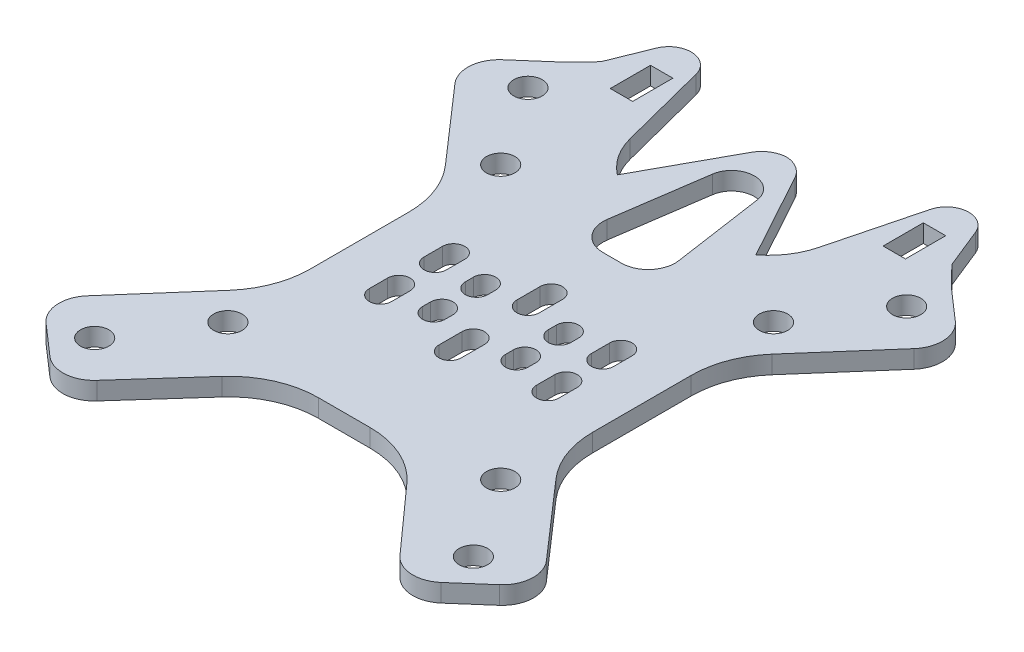
SolidWorks part; units mm, degrees
ref_plane "Alzado" through (0, 0, 0) normal (0, 0, 1) x (1, 0, 0)
ref_plane "Planta" through (0, 0, 0) normal (0, 1, 0) x (1, 0, 0)
ref_plane "Vista lateral" through (0, 0, 0) normal (1, 0, 0) x (0, 0, -1)
sketch "Croquis2" plane through (0, 0, 0) normal (0, 1, 0) x (1, 0, 0)
  line L0 (0, 0) -> (0, 10.4123) construction
  line L5 (0, 0) -> (-13.8586, 0) construction
  line L7 (-18.2653, -12.0856) -> (-25.6658, -20.5534)
  line L14 (-15.7949, 5.505) -> (-15.7949, -5.505)
  line L16 (15.7949, 5.505) -> (15.7949, -5.505)
  line L17 (-15.9969, 16.6536) -> (15.9969, -16.6536) construction
  line L18 (-14.5936, -16.6982) -> (14.5936, 16.6982) construction
  line L20 (-25.3337, -25.492) -> (-21.87, -28.5191)
  line L21 (18.2653, -12.0856) -> (25.6658, -20.5534)
  line L23 (25.3337, -25.492) -> (21.87, -28.5191)
  line L24 (25.3337, 25.492) -> (21.87, 28.5191)
  line L25 (15.4321, 26.7753) -> (15.4536, 26.7998)
  line L26 (18.2653, 12.0856) -> (25.6658, 20.5534)
  line L27 (-25.3337, 25.492) -> (-21.87, 28.5191)
  line L29 (-9.3499, 4.0906) -> (-9.3499, 2.0372) construction
  line L30 (-18.2653, 12.0856) -> (-25.6658, 20.5534)
  line L31 (-21.1669, 24.2194) -> (-23.6019, 27.0055)
  line L36 (-16.5, 33.2505) -> (-14, 33.2505)
  line L37 (-16.5, 33.2505) -> (-16.5, 28.7505)
  line L38 (-16.5, 28.7505) -> (-14, 28.7505)
  line L39 (-14, 33.2505) -> (-14, 28.7505)
  line L45 (-4.6372, 2.84) -> (-4.6372, 1.9423) construction
  line L50 (-8.0999, 4.0906) -> (-8.0999, 2.0372)
  line L51 (-10.5999, 4.0906) -> (-10.5999, 2.0372)
  line L52 (-3.3872, 2.84) -> (-3.3872, 1.9423)
  line L53 (-9.3499, -4.0906) -> (-9.3499, -2.0372) construction
  line L54 (-8.0999, -4.0906) -> (-8.0999, -2.0372)
  line L55 (-10.5999, -4.0906) -> (-10.5999, -2.0372)
  line L56 (-5.8872, 2.84) -> (-5.8872, 1.9423)
  line L57 (-10.5379, 25.0163) -> (-13.0924, 34.9381)
  line L58 (-4.6372, -2.84) -> (-4.6372, -1.9423) construction
  line L59 (-3.3872, -2.84) -> (-3.3872, -1.9423)
  line L60 (-5.8872, -2.84) -> (-5.8872, -1.9423)
  line L61 (9.3499, 4.0906) -> (9.3499, 2.0372) construction
  line L62 (8.0999, 4.0906) -> (8.0999, 2.0372)
  line L63 (10.5999, 4.0906) -> (10.5999, 2.0372)
  line L64 (4.6372, 2.84) -> (4.6372, 1.9423) construction
  line L65 (3.3872, 2.84) -> (3.3872, 1.9423)
  line L66 (5.8872, 2.84) -> (5.8872, 1.9423)
  line L67 (9.3499, -4.0906) -> (9.3499, -2.0372) construction
  line L68 (8.0999, -4.0906) -> (8.0999, -2.0372)
  line L69 (10.5999, -4.0906) -> (10.5999, -2.0372)
  line L70 (4.6372, -2.84) -> (4.6372, -1.9423) construction
  line L71 (3.3872, -2.84) -> (3.3872, -1.9423)
  line L72 (5.8872, -2.84) -> (5.8872, -1.9423)
  line L74 (0, 87.5) -> (0, -87.5) construction
  line L77 (-17.8315, 35.2509) -> (-19.6241, 30.812)
  line L78 (16.5, 28.7505) -> (14, 28.7505)
  line L79 (16.5, 33.2505) -> (16.5, 28.7505)
  line L80 (14, 33.2505) -> (14, 28.7505)
  line L81 (-54.7575, 71.0121) -> (-10.9896, 20.9323) construction
  line L82 (-23.4827, 26.1265) -> (-13.501, 38.2475) construction
  line L83 (25.3337, 25.492) -> (21.87, 28.5191)
  line L84 (-19.6241, 30.812) -> (-21.87, 28.5191)
  line L85 (16.5, 33.2505) -> (14, 33.2505)
  line L87 (19.6241, 30.812) -> (21.87, 28.5191)
  line L88 (17.8315, 35.2509) -> (19.6241, 30.812)
  line L89 (10.7473, 25.8297) -> (13.0924, 34.9381)
  line L90 (-1.0018, 28.1672) -> (1.0018, 28.1672) construction
  line L91 (-16.9315, -28.1869) -> (-10.3397, -20.824)
  line L92 (-2.8893, -17.4942) -> (2.8893, -17.4942)
  line L93 (10.3397, -20.824) -> (16.9315, -28.1869)
  line L94 (0, -5.6537) -> (0, -3.0639) construction
  line L95 (-1.25, -5.6537) -> (-1.25, -3.0639)
  line L96 (1.25, -5.6537) -> (1.25, -3.0639)
  line L97 (0, 5.6537) -> (0, 3.0639) construction
  line L98 (-1.25, 5.6537) -> (-1.25, 3.0639)
  line L99 (1.25, 5.6537) -> (1.25, 3.0639)
  line L100 (-7.7425, 20.7891) -> (-2.4628, 30.4274)
  line L101 (0.1683, 31.9861) -> (1.6089, 31.9861)
  line L102 (1.6089, 31.9861) -> (-1.6089, 31.9861) construction
  line L103 (1.0311, 12.4669) -> (-1.0311, 12.4669)
  line L104 (-3.9997, 15.8997) -> (-2.5002, 26.1856)
  line L105 (3.9997, 15.8997) -> (2.5002, 26.1856)
  line L106 (10.5379, 25.0163) -> (13.0924, 34.9381)
  line L107 (7.7425, 20.7891) -> (2.4628, 30.4274)
  circle A13 centre (-15.25, 15.25) radius 1.59
  circle A14 centre (15.25, 15.25) radius 1.59
  circle A15 centre (15.25, -15.25) radius 1.59
  circle A16 centre (-15.25, -15.25) radius 1.59
  arc A19 (-16.9315, -28.1869) -> (-21.87, -28.5191) centre (-19.5668, -25.8837) cw
  arc A20 (-25.3337, -25.492) -> (-25.6658, -20.5534) centre (-23.0305, -22.8566) cw
  arc A21 (25.3337, -25.492) -> (25.6658, -20.5534) centre (23.0305, -22.8566) ccw
  arc A22 (16.9315, -28.1869) -> (21.87, -28.5191) centre (19.5668, -25.8837) ccw
  arc A24 (25.3337, 25.492) -> (25.6658, 20.5534) centre (23.0305, 22.8566) cw
  arc A25 (-25.3337, 25.492) -> (-25.6658, 20.5534) centre (-23.0305, 22.8566) ccw
  circle A27 centre (-21.1669, 24.2194) radius 1.5875
  circle A28 centre (21.1669, 24.2194) radius 1.5875
  circle A29 centre (21.1669, -24.2194) radius 1.5875
  circle A30 centre (-21.1669, -24.2194) radius 1.5875
  circle A33 centre (21.1669, -24.2194) radius 1.5875
  arc A41 (-8.0999, 4.0906) -> (-10.5999, 4.0906) centre (-9.3499, 4.0906) ccw
  arc A42 (-10.5999, 2.0372) -> (-8.0999, 2.0372) centre (-9.3499, 2.0372) ccw
  arc A43 (-8.0999, -4.0906) -> (-10.5999, -4.0906) centre (-9.3499, -4.0906) cw
  arc A44 (-10.5999, -2.0372) -> (-8.0999, -2.0372) centre (-9.3499, -2.0372) cw
  arc A45 (-3.3872, 2.84) -> (-5.8872, 2.84) centre (-4.6372, 2.84) ccw
  arc A46 (-5.8872, 1.9423) -> (-3.3872, 1.9423) centre (-4.6372, 1.9423) ccw
  arc A47 (-3.3872, -2.84) -> (-5.8872, -2.84) centre (-4.6372, -2.84) cw
  arc A48 (-5.8872, -1.9423) -> (-3.3872, -1.9423) centre (-4.6372, -1.9423) cw
  arc A49 (8.0999, 4.0906) -> (10.5999, 4.0906) centre (9.3499, 4.0906) cw
  arc A50 (10.5999, 2.0372) -> (8.0999, 2.0372) centre (9.3499, 2.0372) cw
  arc A51 (3.3872, 2.84) -> (5.8872, 2.84) centre (4.6372, 2.84) cw
  arc A52 (5.8872, 1.9423) -> (3.3872, 1.9423) centre (4.6372, 1.9423) cw
  arc A53 (8.0999, -4.0906) -> (10.5999, -4.0906) centre (9.3499, -4.0906) ccw
  arc A54 (10.5999, -2.0372) -> (8.0999, -2.0372) centre (9.3499, -2.0372) ccw
  arc A55 (3.3872, -2.84) -> (5.8872, -2.84) centre (4.6372, -2.84) ccw
  arc A56 (5.8872, -1.9423) -> (3.3872, -1.9423) centre (4.6372, -1.9423) ccw
  arc A58 (0, 12.4048) -> (0.0851, 12.404) centre (0.0851, 16.904) ccw
  circle A60 centre (21.1669, 24.2194) radius 1.5875
  arc A61 (-17.8315, 35.2509) -> (-13.0924, 34.9381) centre (-15.5134, 34.3148) cw
  arc A62 (17.8315, 35.2509) -> (13.0924, 34.9381) centre (15.5134, 34.3148) ccw
  arc A63 (1.6089, 31.9861) -> (3.4412, 32.7853) centre (1.6089, 34.4861) ccw construction
  arc A64 (-7.7425, 20.7891) -> (-10.5379, 25.0163) centre (-3.0154, 26.9531) cw
  arc A65 (-2.5169, -16.2439) -> (-10.9896, -20.9323) centre (-2.5169, -26.2439) ccw construction
  arc A66 (10.9896, -20.9323) -> (2.5169, -16.2439) centre (2.5169, -26.2439) ccw construction
  arc A67 (10.3397, -20.824) -> (2.8893, -17.4942) centre (2.8893, -27.4942) ccw
  arc A68 (-10.3397, -20.824) -> (-2.8893, -17.4942) centre (-2.8893, -27.4942) cw
  arc A69 (-1.25, -5.6537) -> (1.25, -5.6537) centre (0, -5.6537) ccw
  arc A70 (1.25, -3.0639) -> (-1.25, -3.0639) centre (0, -3.0639) ccw
  arc A71 (-1.25, 5.6537) -> (1.25, 5.6537) centre (0, 5.6537) cw
  arc A72 (1.25, 3.0639) -> (-1.25, 3.0639) centre (0, 3.0639) cw
  arc A73 (-2.4628, 30.4274) -> (0.1683, 31.9861) centre (0.1683, 28.9861) cw
  arc A74 (-1.0311, 12.4669) -> (-3.9997, 15.8997) centre (-1.0311, 15.4669) cw
  arc A75 (1.0311, 12.4669) -> (3.9997, 15.8997) centre (1.0311, 15.4669) ccw
  arc A76 (-2.5002, 26.1856) -> (2.5002, 26.1856) centre (0, 25.8211) cw
  arc A77 (7.7425, 20.7891) -> (10.5379, 25.0163) centre (3.0154, 26.9531) ccw
  arc A78 (2.4628, 30.4274) -> (-0.1683, 31.9861) centre (-0.1683, 28.9861) ccw
  arc A79 (18.2653, 12.0856) -> (15.7949, 5.505) centre (25.7949, 5.505) ccw
  arc A80 (15.7949, -5.505) -> (18.2653, -12.0856) centre (25.7949, -5.505) ccw
  arc A81 (-18.2653, 12.0856) -> (-15.7949, 5.505) centre (-25.7949, 5.505) cw
  arc A82 (-15.7949, -5.505) -> (-18.2653, -12.0856) centre (-25.7949, -5.505) cw
  point P22 (-19.2347, -30.8223)
  point P25 (-27.9691, -23.1888)
  point P34 (27.9691, -23.1888)
  point P35 (19.2347, -30.8223)
  point P53 (19.2347, 30.8223)
  point P54 (-27.9691, 23.1888)
  point P55 (-19.2347, 30.8223)
  point P65 (-9.3499, 3.0639)
  point P78 (9.0366, 19.1852)
  point P88 (-9.0366, 19.1852)
  point P99 (-9.3499, -3.0639)
  point P109 (-4.6372, 2.3911)
  point P117 (-4.6372, -2.3911)
  point P124 (9.3499, 3.0639)
  point P131 (4.6372, 2.3911)
  point P138 (9.3499, -3.0639)
  point P145 (4.6372, -2.3911)
  point P152 (0, 12.404)
  point P154 (7.2034, 12.404)
  point P157 (-7.2034, 12.404)
  point P160 (0, 26.7782)
  point P169 (16.3904, 27.8718)
  point P173 (7.3586, -17.4942)
  point P176 (-7.3586, -17.4942)
  point P179 (0, -4.3588)
  point P187 (0, 4.3588)
  point P197 (-1.6089, 31.9861)
  point P200 (0, 12.8836)
  point P203 (8.2335, 13.1366)
  point P206 (0, 28.1672)
  point P207 (0, 12.4669)
  point P209 (-8.2335, 13.1366)
  point P217 (15.7949, 9.259)
  point P220 (15.7949, -9.259)
  point P223 (-15.7949, 9.259)
  point P226 (-15.7949, -9.259)
  dimension "D3" = 3.5
  dimension "D5" = 3.18
  dimension "D1" = 15.25
  dimension "D2" = 5.8
  dimension "D9" = 3
  dimension "D7" = 3.175
  dimension "D10" = 2.5
  dimension "D12" = 10
  dimension "D19" = 2.5
  dimension "D8" = 10
  dimension "D4" = 85
  dimension "D6" = 30.5
  dimension "D11" = 2.5
  dimension "D15" = 2.5
  dimension "D16" = 4.5
  dimension "D18" = 14
  dimension "D20" = 3.7002
extrude "Saliente-Extruir1" add sketch "Croquis2" along normal blind 2
sketch "Croquis3" plane through (0, 0, 0) normal (0, 1, 0) x (1, 0, 0)
  line L0 (0, 0) -> (0, 33.3632) construction
sketch "Croquis4" plane through (0, 2, 0) normal (0, 1, 0) x (1, 0, 0)
  line L0 (0, 10) -> (0, -10)
  point P4 (0, 0)
  dimension "D1" = 20
